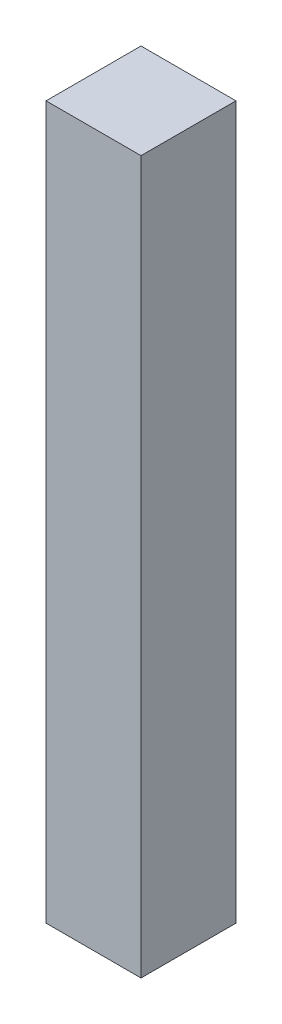
SolidWorks part; units mm, degrees
ref_plane "Front Plane" through (0, 0, 0) normal (0, 0, 1) x (1, 0, 0)
ref_plane "Top Plane" through (0, 0, 0) normal (0, 1, 0) x (1, 0, 0)
ref_plane "Right Plane" through (0, 0, 0) normal (1, 0, 0) x (0, 0, -1)
sketch "Sketch1" plane through (0, 0, 0) normal (0, 0, 1) x (1, 0, 0)
  line L1 (0, 0) -> (5.08, 0)
  line L2 (0, 0) -> (0, 38.1)
  line L3 (0, 38.1) -> (5.08, 38.1)
  line L4 (5.08, 0) -> (5.08, 38.1)
  dimension "D1" = 38.1
  dimension "D2" = 5.08
extrude "Boss-Extrude1" add sketch "Sketch1" along normal blind 5.08
